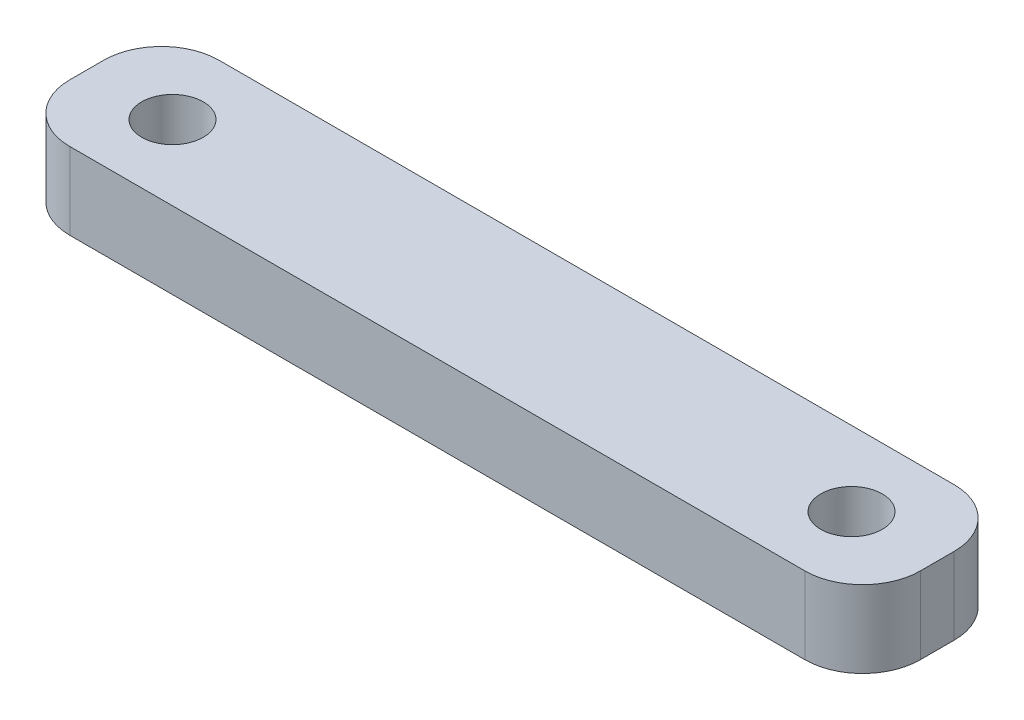
SolidWorks part; units mm, degrees
ref_plane "前视基准面" through (0, 0, 0) normal (0, 0, 1) x (1, 0, 0)
ref_plane "上视基准面" through (0, 0, 0) normal (0, 1, 0) x (1, 0, 0)
ref_plane "右视基准面" through (0, 0, 0) normal (1, 0, 0) x (0, 0, -1)
sketch "草图1" plane through (0, 0, 0) normal (0, 1, 0) x (1, 0, 0)
  line L0 (0, 0) -> (0, 49.5273) construction
  line L1 (22.1089, -3.8813) -> (-22.1089, -3.8813)
  line L2 (22.1089, -3.8813) -> (22.1089, 3.8813)
  line L3 (22.1089, 3.8813) -> (-22.1089, 3.8813)
  line L4 (-22.1089, -3.8813) -> (-22.1089, 3.8813)
  line L5 (22.1089, -3.8813) -> (-22.1089, 3.8813) construction
  line L6 (22.1089, 3.8813) -> (-22.1089, -3.8813) construction
  circle A0 centre (-17.65, 0) radius 1.6
  circle A1 centre (17.65, 0) radius 1.6
  point P0 (0, 0)
  point P12 (-22.1089, 3.8813)
extrude "凸台-拉伸1" add sketch "草图1" along normal blind 4
fillet "圆角1" radius 3 4 edges at (-22.1089, 2, -3.8813) (22.1089, 2, -3.8813) (22.1089, 2, 3.8813) (-22.1089, 2, 3.8813)
